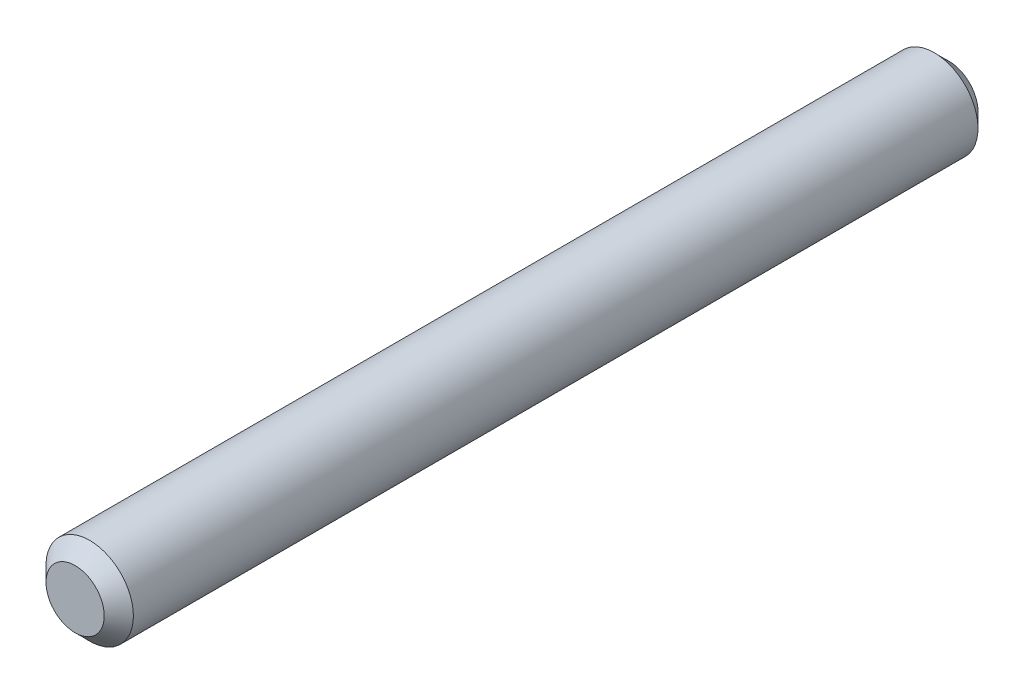
SolidWorks part; units mm, degrees
material "Acier allié inoxydable"
ref_plane "Plan de face" through (0, 0, 0) normal (0, 0, 1) x (1, 0, 0)
ref_plane "Plan de dessus" through (0, 0, 0) normal (0, 1, 0) x (1, 0, 0)
ref_plane "Plan de droite" through (0, 0, 0) normal (1, 0, 0) x (0, 0, -1)
sketch "Esquisse1" plane through (0, 0, 0) normal (0, 0, 1) x (1, 0, 0)
  circle A0 centre (0, 0) radius 1.5
  dimension "D1" = 3
extrude "Boss.-Extru.1" add sketch "Esquisse1" along normal mid plane 30
chamfer "Chanfrein1" distance 0.5 angle 45 2 edges at (1.5, 0, -15) (1.5, 0, 15)
